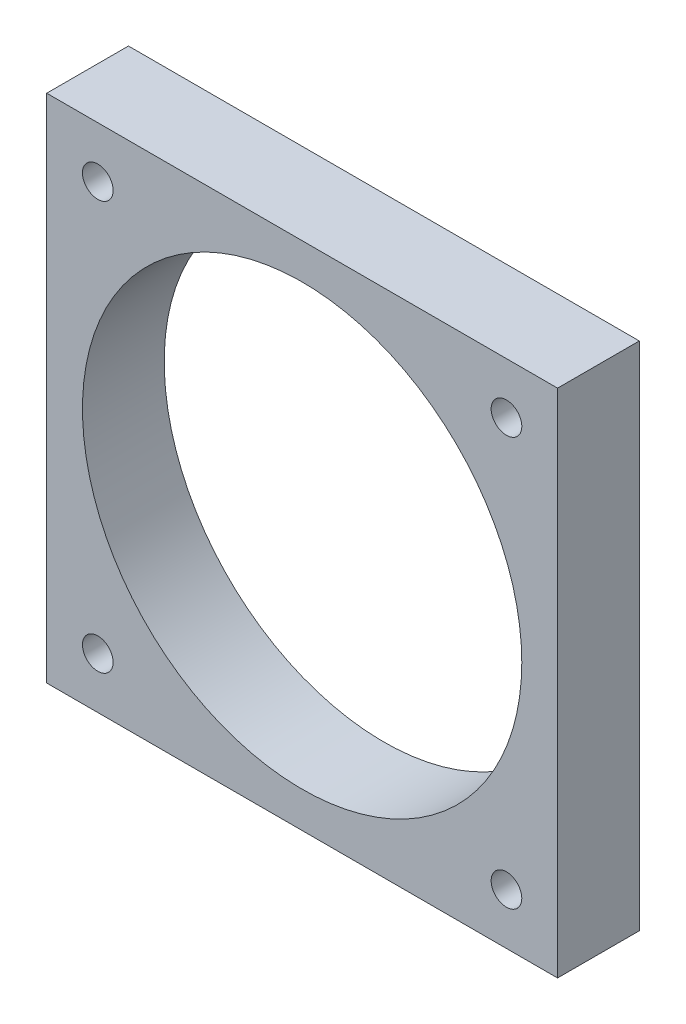
SolidWorks part; units mm, degrees
ref_plane "前视基准面" through (0, 0, 0) normal (0, 0, 1) x (1, 0, 0)
ref_plane "上视基准面" through (0, 0, 0) normal (0, 1, 0) x (1, 0, 0)
ref_plane "右视基准面" through (0, 0, 0) normal (1, 0, 0) x (0, 0, -1)
sketch "草图1" plane through (0, 0, 0) normal (0, 0, 1) x (1, 0, 0)
  line L0 (0, 24.2958) -> (0, -18.2642) construction
  line L1 (-25, 25) -> (25, 25)
  line L2 (-25, 25) -> (-25, -25)
  line L3 (-25, -25) -> (25, -25)
  line L4 (25, 25) -> (25, -25)
  line L5 (-32.2198, 0) -> (32.714, 0) construction
  circle A0 centre (0, 0) radius 21.5
  circle A1 centre (-20, 20) radius 1.5
  circle A2 centre (20, 20) radius 1.5
  circle A3 centre (20, -20) radius 1.5
  circle A4 centre (-20, -20) radius 1.5
  dimension "D1" = 43
  dimension "D6" = 3
  dimension "D8" = 20
  dimension "D2" = 50
  dimension "D3" = 50
  dimension "D4" = 25
  dimension "D5" = 25
  dimension "D7" = 20
extrude "凸台-拉伸1" add sketch "草图1" along normal blind 8
